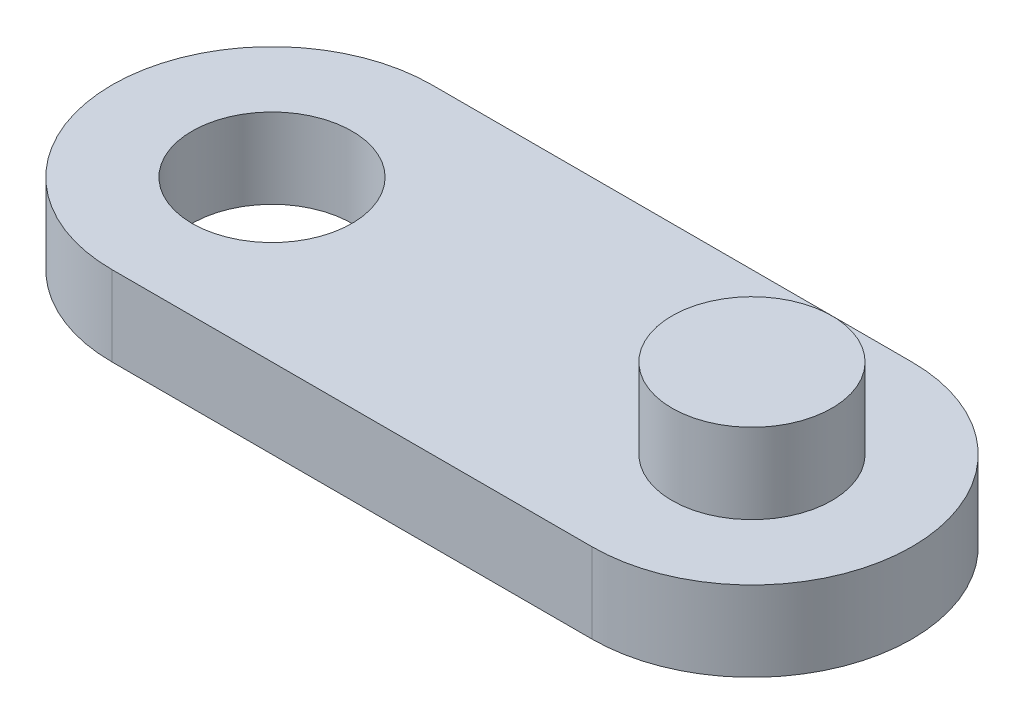
SolidWorks part; units mm, degrees
ref_plane "Front Plane" through (0, 0, 0) normal (0, 0, 1) x (1, 0, 0)
ref_plane "Top Plane" through (0, 0, 0) normal (0, 1, 0) x (1, 0, 0)
ref_plane "Right Plane" through (0, 0, 0) normal (1, 0, 0) x (0, 0, -1)
sketch "Sketch1" plane through (0, 0, 0) normal (0, 1, 0) x (1, 0, 0)
  line L2 (-15, 10) -> (15, 10)
  line L3 (-15, -10) -> (15, -10)
  arc A0 (-15, 10) -> (-15, -10) centre (-15, 0) ccw
  arc A1 (15, -10) -> (15, 10) centre (15, 0) ccw
extrude "Boss-Extrude1" add sketch "Sketch1" along normal blind 5
sketch "Sketch2" plane through (0, 5, 0) normal (0, 1, 0) x (1, 0, 0)
  circle A0 centre (15, 0) radius 5
extrude "Boss-Extrude2" add sketch "Sketch2" along normal blind 5 contours A0
sketch "Sketch3" plane through (0, 5, 0) normal (0, 1, 0) x (1, 0, 0)
  circle A0 centre (-15, 0) radius 5
extrude "Cut-Extrude1" cut sketch "Sketch3" against normal through all
